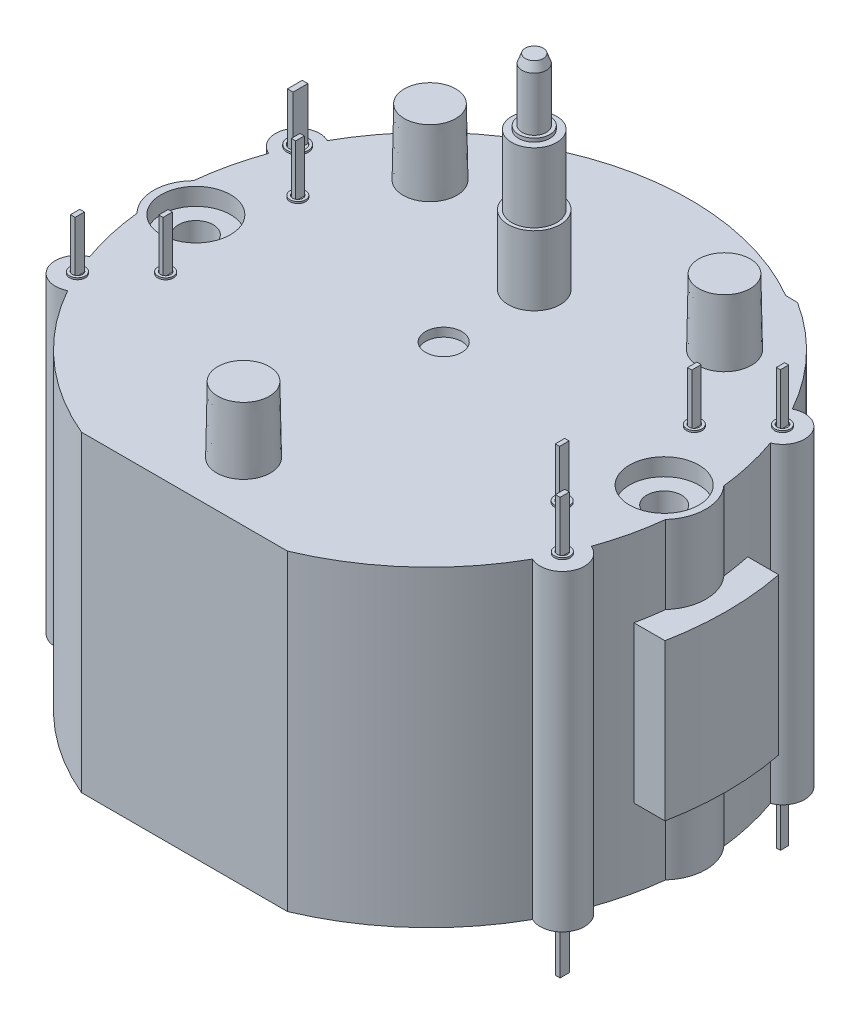
SolidWorks part; units mm, degrees
other "Camera1"
ref_plane "Front Plane" through (0, 0, 0) normal (0, 0, 1) x (1, 0, 0)
ref_plane "Top Plane" through (0, 0, 0) normal (0, 1, 0) x (1, 0, 0)
ref_plane "Right Plane" through (0, 0, 0) normal (1, 0, 0) x (0, 0, -1)
sketch "Sketch1" plane through (0, 0, 0) normal (0, 1, 0) x (1, 0, 0)
  line L0 (-6.4095, -13.4717) -> (6.386, 13.6627) construction
  dimension "D1" = 30
sketch "Sketch2" plane through (0, 0, 0) normal (0, 1, 0) x (1, 0, 0)
  line L0 (-7.7074, 13.2768) -> (-7.0072, 13.2627)
  line L1 (-5.9378, -14.157) -> (5.9378, -14.157)
  line L2 (7.5358, 12.9697) -> (8.236, 12.9555)
  line L3 (-53.4921, -11.3428) -> (-53.4921, 6.8489) construction
  arc A0 (7.5358, 12.9697) -> (-7.0072, 13.2627) centre (0, 0) ccw
  arc A1 (-7.7074, 13.2768) -> (-13.4018, 7.4879) centre (0, 0) ccw
  arc A2 (5.9378, -14.157) -> (13.4018, -7.4879) centre (0, 0) ccw
  arc A3 (-13.4018, 7.4879) -> (-14.4583, 5.1609) centre (-13.9786, 6.3464) ccw
  arc A4 (14.4583, 5.1609) -> (13.4018, 7.4879) centre (13.9786, 6.3464) ccw
  arc A5 (13.4018, -7.4879) -> (14.4583, -5.1609) centre (13.9786, -6.3464) ccw
  arc A6 (-14.4583, -5.1609) -> (-13.4018, -7.4879) centre (-13.9786, -6.3464) ccw
  arc A7 (-13.4018, -7.4879) -> (-5.9378, -14.157) centre (0, 0) ccw
  arc A8 (-14.4583, 5.1609) -> (-15.2651, 1.6294) centre (0, 0) ccw
  arc A9 (13.4018, 7.4879) -> (8.236, 12.9555) centre (0, 0) ccw
  arc A10 (14.4583, -5.1609) -> (15.2595, -1.6805) centre (0, 0) ccw
  arc A11 (15.2595, -1.6805) -> (15.2595, 1.6805) centre (13.4018, 0) ccw
  arc A12 (15.2595, 1.6805) -> (14.4583, 5.1609) centre (0, 0) ccw
  arc A13 (-15.2651, 1.6294) -> (-15.2651, -1.6294) centre (-13.6137, 0) ccw
  arc A14 (-15.2651, -1.6294) -> (-14.4583, -5.1609) centre (0, 0) ccw
  dimension "D1" = 15
  dimension "D2" = 15.3518
  dimension "D3" = 5.9378
  dimension "D4" = 7.5358
  dimension "D5" = 8.236
  dimension "D6" = 18.1917
extrude "Boss-Extrude1" add sketch "Sketch2" along normal blind 18
sketch "Sketch3" plane through (0, 18, 0) normal (0, 1, 0) x (1, 0, 0)
  circle A0 centre (0, 6.0097) radius 1.5
  dimension "D1" = 3
extrude "Boss-Extrude2" add sketch "Sketch3" along normal blind 4 separate body
sketch "Sketch4" plane through (0, 22, 0) normal (0, 1, 0) x (1, 0, 0)
  circle A0 centre (0, 6.0097) radius 1.3
  dimension "D1" = 2.6
extrude "Boss-Extrude3" add sketch "Sketch4" along normal blind 4
sketch "Sketch5" plane through (0, 26, 0) normal (0, 1, 0) x (1, 0, 0)
  circle A0 centre (0, 6.0097) radius 0.7
  dimension "D1" = 1.4
extrude "Boss-Extrude4" add sketch "Sketch5" along normal blind 3.8
chamfer "Chamfer1" distance 0.5 angle 20 1 edges at (0, 29.8, -5.3097)
sketch "Sketch6" plane through (0, 18, 0) normal (0, 1, 0) x (1, 0, 0)
  line L0 (0, 6.0097) -> (0, 10.7931) construction
  circle A0 centre (0, -10.75) radius 1.55
  circle A1 centre (8.49, 8.49) radius 1.55
  circle A2 centre (-8.49, 8.49) radius 1.55
  dimension "D1" = 3.1
  dimension "D3" = 3.1
  dimension "D5" = 16.98
  dimension "D2" = 10.75
  dimension "D4" = 19.24
extrude "Boss-Extrude5" add sketch "Sketch6" along normal blind 3.8 draft 1
sketch "Sketch7" plane through (0, 26, 0) normal (0, 1, 0) x (1, 0, 0)
  circle A0 centre (0, 6.0097) radius 0.7 construction
  circle A1 centre (0, 6.0097) radius 0.7
extrude "Extrude-Thin1" add sketch "Sketch7" along normal blind 0.2 thin
sketch "Sketch8" plane through (0, 0, 0) normal (0, 1, 0) x (1, 0, 0)
  line L0 (-16.7953, 3.3246) -> (16.7804, 3.3246)
  line L1 (16.7953, -3.2484) -> (-16.7953, -3.2484)
  arc A0 (-16.7804, 3.3246) -> (-16.7953, -3.2484) centre (0, 0) ccw
  arc A1 (16.7953, -3.2484) -> (16.7804, 3.3246) centre (0, 0) ccw
extrude "Boss-Extrude6" add sketch "Sketch8" along normal blind 9 from offset 4.5 contours L1 A1 L0 A0
sketch "Sketch9" plane through (0, 18, 0) normal (0, 1, 0) x (1, 0, 0)
  line L1 (-11.43, 3.81) -> (11.43, 3.81) construction
  line L2 (-11.43, 3.81) -> (-11.43, -3.81) construction
  line L3 (-11.43, -3.81) -> (11.43, -3.81) construction
  line L4 (11.43, 3.81) -> (11.43, -3.81) construction
  line L5 (-11.43, 3.81) -> (11.43, -3.81) construction
  line L6 (-11.43, -3.81) -> (11.43, 3.81) construction
  circle A0 centre (-11.43, 3.81) radius 0.3
  circle A1 centre (-11.43, -3.81) radius 0.3
  circle A2 centre (11.43, -3.81) radius 0.3
  circle A3 centre (11.43, 3.81) radius 0.3
  circle A4 centre (-13.9786, 6.3464) radius 0.4579
  circle A5 centre (-13.9786, -6.3464) radius 0.3
  circle A6 centre (13.9786, -6.3464) radius 0.3
  circle A7 centre (13.9786, 6.3464) radius 0.3
  point P0 (0, 0)
  dimension "D3" = 0.6
  dimension "D1" = 7.62
  dimension "D2" = 22.86
extrude "Extrude-Thin2" add sketch "Sketch9" along normal blind 0.1 and the other way blind 18.1 thin
sketch "Sketch10" plane through (0, 18, 0) normal (0, 1, 0) x (1, 0, 0)
  line L1 (-11.555, 4.06) -> (-11.305, 4.06)
  line L2 (-11.555, 4.06) -> (-11.555, 3.56)
  line L3 (-11.555, 3.56) -> (-11.305, 3.56)
  line L4 (-11.305, 4.06) -> (-11.305, 3.56)
  line L5 (-11.555, 4.06) -> (-11.305, 3.56) construction
  line L6 (-11.555, 3.56) -> (-11.305, 4.06) construction
  line L7 (-11.555, -3.5373) -> (-11.305, -3.5373)
  line L8 (-11.555, -3.5373) -> (-11.555, -4.0827)
  line L9 (-11.555, -4.0827) -> (-11.305, -4.0827)
  line L10 (-11.305, -3.5373) -> (-11.305, -4.0827)
  line L11 (-11.555, -3.5373) -> (-11.305, -4.0827) construction
  line L12 (-11.555, -4.0827) -> (-11.305, -3.5373) construction
  line L13 (11.305, -3.5373) -> (11.555, -3.5373)
  line L14 (11.305, -3.5373) -> (11.305, -4.0827)
  line L15 (11.305, -4.0827) -> (11.555, -4.0827)
  line L16 (11.555, -3.5373) -> (11.555, -4.0827)
  line L17 (11.305, -3.5373) -> (11.555, -4.0827) construction
  line L18 (11.305, -4.0827) -> (11.555, -3.5373) construction
  line L19 (11.305, 4.0827) -> (11.555, 4.0827)
  line L20 (11.305, 4.0827) -> (11.305, 3.5373)
  line L21 (11.305, 3.5373) -> (11.555, 3.5373)
  line L22 (11.555, 4.0827) -> (11.555, 3.5373)
  line L23 (11.305, 4.0827) -> (11.555, 3.5373) construction
  line L24 (11.305, 3.5373) -> (11.555, 4.0827) construction
  line L25 (13.863, 6.5846) -> (14.0941, 6.5846)
  line L26 (13.863, 6.5846) -> (13.863, 6.1083)
  line L27 (13.863, 6.1083) -> (14.0941, 6.1083)
  line L28 (14.0941, 6.5846) -> (14.0941, 6.1083)
  line L29 (13.863, 6.5846) -> (14.0941, 6.1083) construction
  line L30 (13.863, 6.1083) -> (14.0941, 6.5846) construction
  line L31 (-14.1412, 6.7744) -> (-13.816, 6.7744)
  line L32 (-14.1412, 6.7744) -> (-14.1412, 5.9184)
  line L33 (-14.1412, 5.9184) -> (-13.816, 5.9184)
  line L34 (-13.816, 6.7744) -> (-13.816, 5.9184)
  line L35 (-14.1412, 6.7744) -> (-13.816, 5.9184) construction
  line L36 (-14.1412, 5.9184) -> (-13.816, 6.7744) construction
  line L37 (-14.1136, -6.0785) -> (-13.8436, -6.0785)
  line L38 (-14.1136, -6.0785) -> (-14.1136, -6.6143)
  line L39 (-14.1136, -6.6143) -> (-13.8436, -6.6143)
  line L40 (-13.8436, -6.0785) -> (-13.8436, -6.6143)
  line L41 (-14.1136, -6.0785) -> (-13.8436, -6.6143) construction
  line L42 (-14.1136, -6.6143) -> (-13.8436, -6.0785) construction
  line L43 (13.8436, -6.0785) -> (14.1136, -6.0785)
  line L44 (13.8436, -6.0785) -> (13.8436, -6.6143)
  line L45 (13.8436, -6.6143) -> (14.1136, -6.6143)
  line L46 (14.1136, -6.0785) -> (14.1136, -6.6143)
  line L47 (13.8436, -6.0785) -> (14.1136, -6.6143) construction
  line L48 (13.8436, -6.6143) -> (14.1136, -6.0785) construction
  circle A0 centre (-11.43, -3.81) radius 0.3 construction
  circle A1 centre (11.43, -3.81) radius 0.3 construction
  circle A2 centre (11.43, 3.81) radius 0.3 construction
  circle A3 centre (-13.9786, 6.3464) radius 0.4579 construction
  circle A4 centre (-13.9786, -6.3464) radius 0.3 construction
  circle A5 centre (13.9786, -6.3464) radius 0.3 construction
  point P0 (-11.43, 3.81)
  point P6 (-11.43, -3.81)
  point P14 (11.43, -3.81)
  point P22 (11.43, 3.81)
  point P30 (13.9786, 6.3464)
  point P36 (-13.9786, 6.3464)
  point P44 (-13.9786, -6.3464)
  point P52 (13.9786, -6.3464)
  dimension "D1" = 0.5
  dimension "D2" = 0.25
extrude "Boss-Extrude11" add sketch "Sketch10" along normal blind 3 and the other way blind 21 separate body contours L10 L7 L8 L9 | L4 L1 L2 L3 | L22 L19 L20 L21 | L16 L13 L14 L15 | L46 L43 L44 L45 | L40 L37 L38 L39 | L34 L31 L32 L33 | L28 L25 L26 L27
hole_wizard "Hole1" positions "Sketch11" profile "Sketch12" legacy
sketch "Sketch11" plane through (0, 18, 0) normal (0, 1, 0) x (1, 0, 0)
  point P0 (-13.5, 0)
  point P3 (13.5, 0)
  point P7 (0, 0)
  point P8 (-13.6137, 0)
  point P9 (0, 0)
  point P10 (0, 0)
  point P11 (0, 0)
  point P12 (0, 0)
  point P14 (0, 0)
  dimension "D1" = 27
  dimension "D2" = 13.5
sketch "Sketch12" plane through (-13.5, 18, 0) normal (1, 0, 0) x (0, 0, 1)
  line L0 (0, 0) -> (0, 9)
  line L1 (0, 9) -> (1, 9)
  line L2 (1, 9) -> (1, 1)
  line L3 (1, 1) -> (2, 1)
  line L4 (2, 1) -> (2, 0)
  line L5 (2, 0) -> (0, 0)
  line L6 (0, 110) -> (0, -10) construction
  dimension "Diameter" = 2
  dimension "Depth" = 9
  dimension "C-Bore Diameter" = 4
  dimension "C-Bore Depth" = 1
ref_plane "Plane1" through (0, 9, 0) normal (0, 1, 0) x (1, 0, 0)
mirror "Mirror1" about plane through (0, 9, 0) normal (0, 1, 0) of "Hole1"
sketch "Sketch13" plane through (0, 18, 0) normal (0, 1, 0) x (1, 0, 0)
  circle A0 centre (0, 0.789) radius 1.0436
extrude "Cut-Extrude1" cut sketch "Sketch13" against normal blind 0.5
sketch "Footprint Sketch" plane through (0, 18, 0) normal (0, 1, 0) x (1, 0, 0)
  line L0 (-6.0376, -14.657) -> (6.0376, -14.657)
  line L1 (8.3848, 13.4526) -> (7.674, 13.467)
  line L2 (-7.1253, 13.7652) -> (-7.8361, 13.7795)
  line L3 (-7.0072, 13.2627) -> (-7.7074, 13.2768)
  line L4 (-5.9378, -14.157) -> (5.9378, -14.157)
  line L5 (8.236, 12.9555) -> (7.5358, 12.9697)
  line L6 (-7.0072, 13.2627) -> (-7.7074, 13.2768)
  line L7 (-5.9378, -14.157) -> (5.9378, -14.157)
  line L8 (8.236, 12.9555) -> (7.5358, 12.9697)
  circle A0 centre (-13.97, 6.36) radius 0.4
  circle A1 centre (-13.97, -6.36) radius 0.4
  circle A2 centre (13.97, 6.36) radius 0.4
  circle A3 centre (13.97, -6.36) radius 0.4
  circle A4 centre (-11.43, 3.81) radius 0.4
  circle A5 centre (11.43, 3.81) radius 0.4
  circle A6 centre (-11.43, -3.81) radius 0.4
  circle A7 centre (11.43, -3.81) radius 0.4
  circle A8 centre (0, 6) radius 2.3
  circle A9 centre (-8.49, 8.49) radius 1.5
  circle A10 centre (8.49, 8.49) radius 1.5
  circle A11 centre (0, -10.75) radius 1.5
  circle A13 centre (-13.5, 0) radius 0.9
  circle A14 centre (13.5, 0) radius 0.9
  arc A15 (-13.6313, -8.0911) -> (-6.0376, -14.657) centre (0, 0) ccw
  arc A16 (6.0376, -14.657) -> (13.6313, -8.0911) centre (0, 0) ccw
  arc A17 (13.6313, -8.0911) -> (15.0635, -4.9367) centre (13.9786, -6.3464) ccw
  arc A18 (15.0635, -4.9367) -> (15.7388, -1.8891) centre (0, 0) ccw
  arc A19 (15.7388, -1.8891) -> (15.7388, 1.8891) centre (13.4018, 0) ccw
  arc A20 (15.7388, 1.8891) -> (15.0635, 4.9367) centre (0, 0) ccw
  arc A21 (15.0635, 4.9367) -> (13.6313, 8.0911) centre (13.9786, 6.3464) ccw
  arc A22 (13.6313, 8.0911) -> (8.3848, 13.4526) centre (0, 0) ccw
  arc A23 (7.674, 13.467) -> (-7.1253, 13.7652) centre (0, 0) ccw
  arc A24 (-7.8361, 13.7795) -> (-13.6313, 8.0911) centre (0, 0) ccw
  arc A25 (-13.6313, 8.0911) -> (-15.0635, 4.9367) centre (-13.9786, 6.3464) ccw
  arc A26 (-15.0635, 4.9367) -> (-15.7437, 1.848) centre (0, 0) ccw
  arc A27 (-15.7437, 1.848) -> (-15.7437, -1.848) centre (-13.6137, 0) ccw
  arc A28 (-15.7437, -1.848) -> (-15.0635, -4.9367) centre (0, 0) ccw
  arc A29 (-15.0635, -4.9367) -> (-13.6313, -8.0911) centre (-13.9786, -6.3464) ccw
  arc A30 (7.5358, 12.9697) -> (-7.0072, 13.2627) centre (0, 0) ccw
  arc A31 (-7.7074, 13.2768) -> (-13.4018, 7.4879) centre (0, 0) ccw
  arc A32 (-13.4018, 7.4879) -> (-14.4583, 5.1609) centre (-13.9786, 6.3464) ccw
  arc A33 (-14.4583, 5.1609) -> (-15.2651, 1.6294) centre (0, 0) ccw
  arc A34 (-15.2651, 1.6294) -> (-15.2651, -1.6294) centre (-13.6137, 0) ccw
  arc A35 (-15.2651, -1.6294) -> (-14.4583, -5.1609) centre (0, 0) ccw
  arc A36 (-14.4583, -5.1609) -> (-13.4018, -7.4879) centre (-13.9786, -6.3464) ccw
  arc A37 (-13.4018, -7.4879) -> (-5.9378, -14.157) centre (0, 0) ccw
  arc A38 (5.9378, -14.157) -> (13.4018, -7.4879) centre (0, 0) ccw
  arc A39 (13.4018, -7.4879) -> (14.4583, -5.1609) centre (13.9786, -6.3464) ccw
  arc A40 (14.4583, -5.1609) -> (15.2595, -1.6805) centre (0, 0) ccw
  arc A41 (15.2595, -1.6805) -> (15.2595, 1.6805) centre (13.4018, 0) ccw
  arc A42 (15.2595, 1.6805) -> (14.4583, 5.1609) centre (0, 0) ccw
  arc A43 (14.4583, 5.1609) -> (13.4018, 7.4879) centre (13.9786, 6.3464) ccw
  arc A44 (13.4018, 7.4879) -> (8.236, 12.9555) centre (0, 0) ccw
  arc A45 (7.5358, 12.9697) -> (-7.0072, 13.2627) centre (0, 0) ccw
  arc A46 (-7.7074, 13.2768) -> (-13.4018, 7.4879) centre (0, 0) ccw
  arc A47 (-13.4018, 7.4879) -> (-14.4583, 5.1609) centre (-13.9786, 6.3464) ccw
  arc A48 (-14.4583, 5.1609) -> (-15.2651, 1.6294) centre (0, 0) ccw
  arc A49 (-15.2651, 1.6294) -> (-15.2651, -1.6294) centre (-13.6137, 0) ccw
  arc A50 (-15.2651, -1.6294) -> (-14.4583, -5.1609) centre (0, 0) ccw
  arc A51 (-14.4583, -5.1609) -> (-13.4018, -7.4879) centre (-13.9786, -6.3464) ccw
  arc A52 (-13.4018, -7.4879) -> (-5.9378, -14.157) centre (0, 0) ccw
  arc A53 (5.9378, -14.157) -> (13.4018, -7.4879) centre (0, 0) ccw
  arc A54 (13.4018, -7.4879) -> (14.4583, -5.1609) centre (13.9786, -6.3464) ccw
  arc A55 (14.4583, -5.1609) -> (15.2595, -1.6805) centre (0, 0) ccw
  arc A56 (15.2595, -1.6805) -> (15.2595, 1.6805) centre (13.4018, 0) ccw
  arc A57 (15.2595, 1.6805) -> (14.4583, 5.1609) centre (0, 0) ccw
  arc A58 (14.4583, 5.1609) -> (13.4018, 7.4879) centre (13.9786, 6.3464) ccw
  arc A59 (13.4018, 7.4879) -> (8.236, 12.9555) centre (0, 0) ccw
  circle A60 centre (0, 0) radius 0.389
  point P25 (0, 0)
  dimension "D1" = 0.8
  dimension "D10" = 4.6
  dimension "D12" = 3
  dimension "D17" = 1.8
  dimension "D2" = 13.97
  dimension "D3" = 27.94
  dimension "D4" = 12.72
  dimension "D5" = 6.36
  dimension "D6" = 22.86
  dimension "D7" = 7.62
  dimension "D8" = 11.43
  dimension "D9" = 3.81
  dimension "D11" = 6
  dimension "D13" = 16.98
  dimension "D14" = 8.49
  dimension "D15" = 2.49
  dimension "D16" = 16.75
  dimension "D18" = 27
  dimension "D19" = 13.5
  dimension "D20" = 0
  dimension "D21" = 0.5
equation "\"D2@Footprint Sketch\" = \"D3@Footprint Sketch\" / 2"
equation "\"D5@Footprint Sketch\" = \"D4@Footprint Sketch\" / 2"
equation "\"D8@Footprint Sketch\" = \"D6@Footprint Sketch\" / 2"
equation "\"D9@Footprint Sketch\" = \"D7@Footprint Sketch\" / 2"
equation "\"D14@Footprint Sketch\"=\"D13@Footprint Sketch\"/2"
equation "\"D19@Footprint Sketch\"=\"D18@Footprint Sketch\"/2"
equation "\"D2@Sketch11\"=\"D1@Sketch11\"/2"
